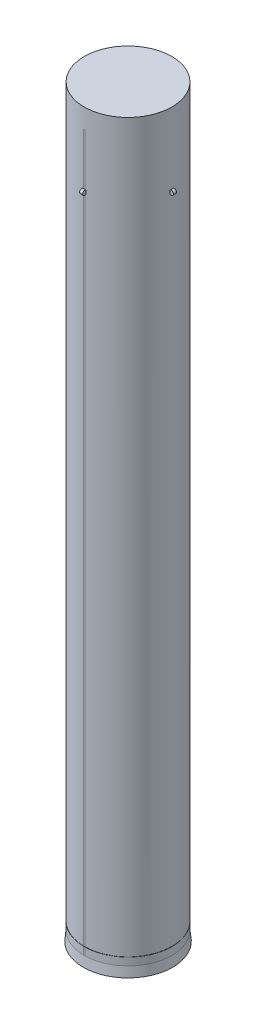
SolidWorks part; units mm, degrees
ref_plane "Front Plane" through (0, 0, 0) normal (0, 0, 1) x (1, 0, 0)
ref_plane "Top Plane" through (0, 0, 0) normal (0, 1, 0) x (1, 0, 0)
ref_plane "Right Plane" through (0, 0, 0) normal (1, 0, 0) x (0, 0, -1)
sketch "Sketch1" plane through (0, 0, 0) normal (0, 0, 1) x (1, 0, 0)
  line L0 (0, 0) -> (0, 76500) construction
  line L1 (0, 76500) -> (4500, 76500)
  line L2 (4500, 76500) -> (4500, 1000)
  line L3 (4500, 1000) -> (4600, 0)
  line L4 (4600, 0) -> (4300, 0)
  line L5 (4300, 0) -> (4300, 1000)
  line L6 (4300, 1000) -> (4300, 73000)
  line L7 (4300, 73000) -> (0, 75000)
  line L8 (0, 75000) -> (0, 76500)
revolve "Revolve1" add sketch "Sketch1" angle 360 about L0
sketch "Sketch2" plane through (0, 0, 0) normal (0, 0, 1) x (1, 0, 0)
  line L0 (0, 0) -> (0, 76500) construction
  line L1 (4500, 76500) -> (-4500, 76500) construction
  circle A0 centre (4506, 1800) radius 10
revolve "Revolve2" add sketch "Sketch2" angle 360 about L0
sketch "Sketch3" plane through (0, 0, 0) normal (0, 0, 1) x (1, 0, 0)
  line L0 (0, 0) -> (0, 76500) construction
  line L1 (4500, 76500) -> (-4500, 76500) construction
  line L2 (0, 45000) -> (3650, 41350)
  line L3 (3650, 41350) -> (4300, 41700)
  line L4 (4300, 41700) -> (0, 45000)
  line L5 (0, 4500) -> (3650, 1698.8372)
  line L6 (3650, 1698.8372) -> (4300, 1100)
  line L7 (4300, 1100) -> (0, 4500)
sketch "Sketch4" plane through (0, 0, 0) normal (0, 0, 1) x (1, 0, 0)
  line L0 (0, 0) -> (0, 76500) construction
  line L1 (0, 74000) -> (0, 2500)
  line L2 (0, 2500) -> (420, 2500)
  line L3 (420, 2500) -> (0, 74000)
  line L4 (0, 74000) -> (480, 74000)
sketch "Sketch5" plane through (0, 0, 0) normal (0, 0, 1) x (1, 0, 0)
  line L0 (0, 0) -> (0, 4500) construction
  line L1 (0, 2250) -> (0, 0)
  line L2 (0, 0) -> (580, -450)
  line L3 (580, -450) -> (0, 2250)
  line L4 (0, 2250) -> (0, 3000)
  line L5 (580, 2250) -> (3280, -450)
  line L6 (3280, -450) -> (2350, -450)
  line L7 (2350, -450) -> (580, 2250)
  line L8 (580, 2250) -> (1600, 2600)
  line L9 (2350, 2600) -> (3280, -450)
  line L10 (3280, -450) -> (4150, -450)
  line L11 (4150, -450) -> (2350, 2600)
  line L12 (2350, 2600) -> (3250, 2400)
sketch "Sketch6" plane through (0, 0, 0) normal (0, 0, 1) x (1, 0, 0)
  circle A0 centre (4600, 69000) radius 220
extrude "Boss-Extrude1" add sketch "Sketch6" along normal mid plane 320
pattern_circular "CirPattern1" count 4 over 360 about axis through (0, 0, 0) along (0, 1, 0) of "Boss-Extrude1"
sketch "Sketch7" plane through (0, 0, 0) normal (1, 0, 0) x (0, 0, -1)
  line L0 (4400, 74500) -> (4500, 74500)
  line L1 (4500, 69195.9592) -> (4500, 76500) construction
  line L2 (4500, 74500) -> (4500, 1000)
  line L3 (4500, 1000) -> (-4500, 1000) construction
  line L4 (4500, 1000) -> (4400, 1000)
  line L5 (4400, 1000) -> (4400, 74500)
  line L6 (-4500, 74500) -> (-4500, 1000)
  line L7 (-4500, 76500) -> (-4500, 69195.9592) construction
  line L8 (-4500, 1000) -> (-4400, 1000)
  line L9 (-4400, 1000) -> (-4500, 74500)
extrude "Boss-Extrude2" add sketch "Sketch7" along normal mid plane 200
